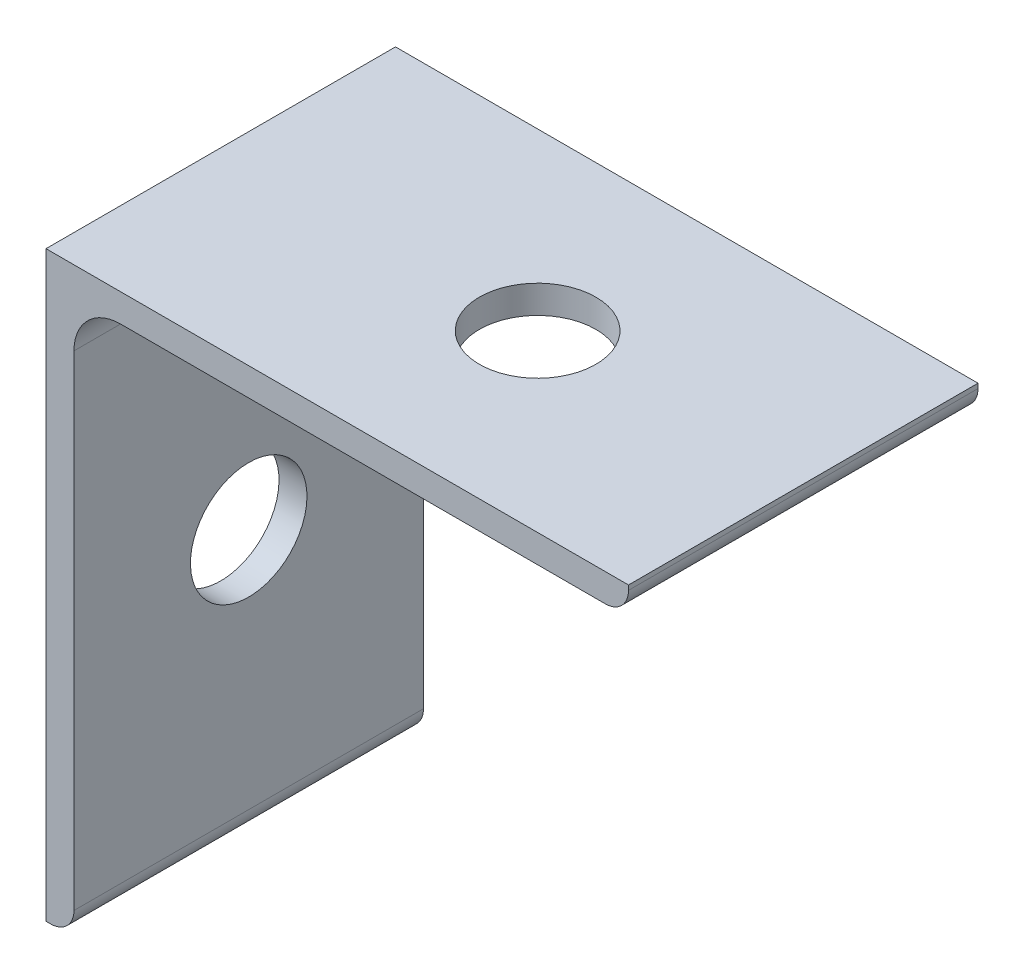
SolidWorks part; units mm, degrees
material "ASTM A36 Aço"
ref_plane "Plano frontal" through (0, 0, 0) normal (0, 0, 1) x (1, 0, 0)
ref_plane "Plano superior" through (0, 0, 0) normal (0, 1, 0) x (1, 0, 0)
ref_plane "Plano direito" through (0, 0, 0) normal (1, 0, 0) x (0, 0, -1)
sketch "Esboço1" plane through (0, 0, 0) normal (0, 0, 1) x (1, 0, 0)
  line L0 (98.7833, -3.5692) -> (98.7833, 17.2308)
  line L1 (97.5833, 20.4308) -> (122.5833, 20.4308)
  line L2 (97.5833, 20.4308) -> (97.5833, -4.5692)
  line L3 (97.5833, -4.5692) -> (97.7833, -4.5692)
  line L4 (122.5833, 20.4308) -> (122.5833, 20.2308)
  line L5 (121.5833, 19.2308) -> (100.7833, 19.2308)
  arc A0 (98.7833, -3.5692) -> (97.7833, -4.5692) centre (97.7833, -3.5692) cw
  arc A1 (121.5833, 19.2308) -> (122.5833, 20.2308) centre (121.5833, 20.2308) ccw
  arc A2 (100.7833, 19.2308) -> (98.7833, 17.2308) centre (100.7833, 17.2308) ccw
  point P8 (98.7833, -4.5692)
  point P11 (122.5833, 19.2308)
  dimension "D5" = 1
  dimension "D6" = 2
  dimension "D1" = 25
  dimension "D2" = 25
  dimension "D3" = 1.2
  dimension "D4" = 1.2
extrude "Ressalto-extrusão1" add sketch "Esboço1" along normal blind 15
sketch "Esboço2" plane through (0, 19.2308, 0) normal (0, -1, 0) x (1, 0, 0)
  line L0 (121.5833, 0) -> (100.7833, 15) construction
  circle A0 centre (111.1833, 7.5) radius 2.5
  dimension "D1" = 5
extrude "Corte-extrusão1" cut sketch "Esboço2" against normal through all
sketch "Esboço3" plane through (98.7833, 0, 0) normal (1, 0, 0) x (0, 0, -1)
  line L0 (0, 17.2308) -> (-15, -3.5692) construction
  circle A0 centre (-7.5, 6.8308) radius 2.5
  dimension "D1" = 5
extrude "Corte-extrusão2" cut sketch "Esboço3" against normal through all
